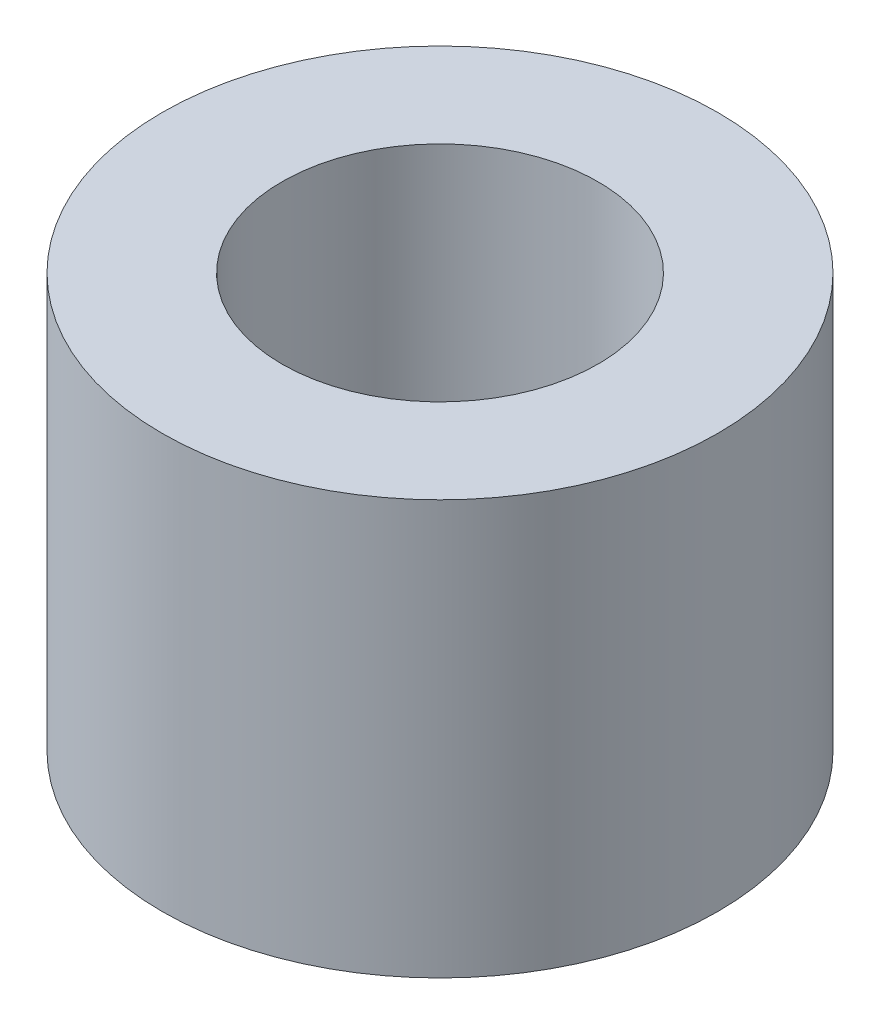
SolidWorks part; units mm, degrees
material "Copper"
ref_plane "Front Plane" through (0, 0, 0) normal (0, 0, 1) x (1, 0, 0)
ref_plane "Top Plane" through (0, 0, 0) normal (0, 1, 0) x (1, 0, 0)
ref_plane "Right Plane" through (0, 0, 0) normal (1, 0, 0) x (0, 0, -1)
sketch "Sketch1" plane through (0, 0, 0) normal (1, 0, 0) x (0, 0, -1)
  line L0 (0, 16.8068) -> (0, -12.267) construction
  line L1 (-12.75, 13.7642) -> (-12.75, -11.1562) construction
  line L2 (9.1278, 0) -> (-20.5739, 0) construction
  line L3 (-7.25, 13.7642) -> (-7.25, -10.7699) construction
  line L4 (-12.75, 9.5) -> (-7.25, 9.5) construction
  line L5 (-12.75, -9.5) -> (-7.25, -9.5) construction
  line L7 (-12.75, 9.5) -> (-7.25, 9.5)
  line L8 (-12.75, 9.5) -> (-12.75, -9.5)
  line L9 (-12.75, -9.5) -> (-7.25, -9.5)
  line L10 (-7.25, 9.5) -> (-7.25, -9.5)
  dimension "D1" = 12.75
  dimension "D2" = 7.25
  dimension "D3" = 9.5
revolve "Revolve3" add sketch "Sketch1" angle 360 about L0
